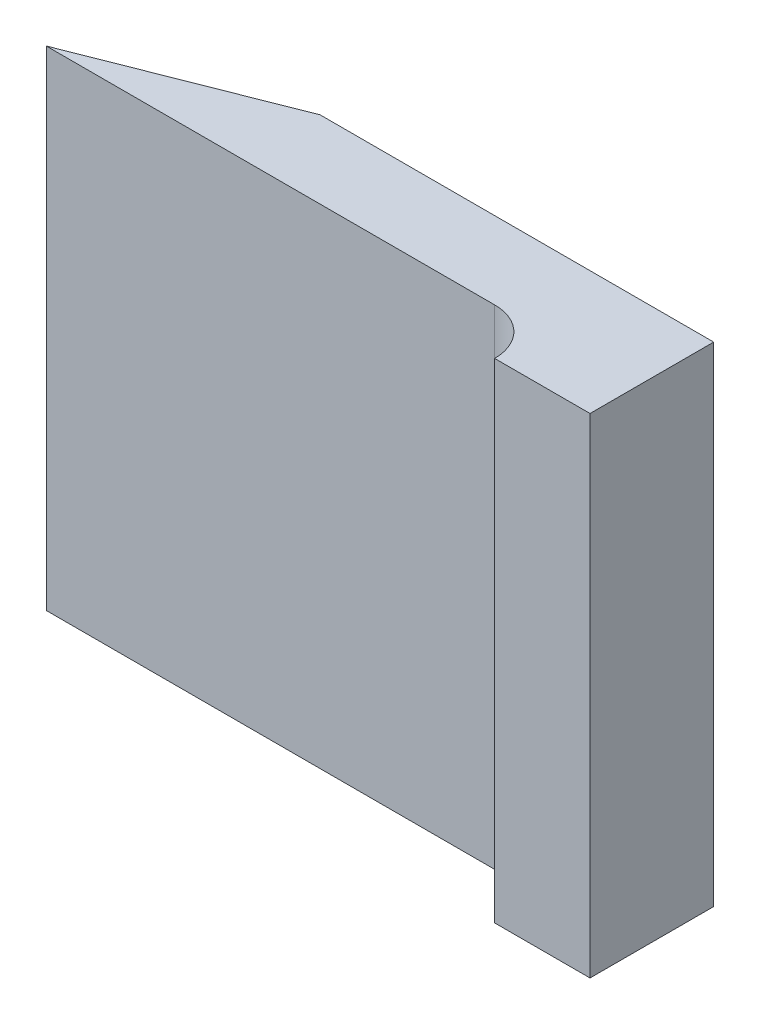
SolidWorks part; units mm, degrees
material "ABS PC"
ref_plane "Front Plane" through (0, 0, 0) normal (0, 0, 1) x (1, 0, 0)
ref_plane "Top Plane" through (0, 0, 0) normal (0, 1, 0) x (1, 0, 0)
ref_plane "Right Plane" through (0, 0, 0) normal (1, 0, 0) x (0, 0, -1)
sketch "Sketch1" plane through (0, 0, 0) normal (0, 0, 1) x (1, 0, 0)
  line L0 (-18.3518, 34.7899) -> (-18.3518, -5.368)
  line L1 (-18.3518, -5.368) -> (30.1209, -5.368)
  line L2 (30.1209, -5.368) -> (30.1209, 34.7899)
  line L3 (30.1209, 34.7899) -> (-18.3518, 34.7899)
extrude "Boss-Extrude1" add sketch "Sketch1" along normal blind 12.7
sketch "Sketch3" plane through (0, 0, 12.7) normal (0, 0, 1) x (1, 0, 0)
  line L0 (-18.3518, -5.368) -> (30.1209, -5.368) construction
  line L1 (-18.3518, 34.7899) -> (22.2882, 34.7899)
  line L2 (-18.3518, 34.7899) -> (-18.3518, -5.368)
  line L3 (-18.3518, -5.368) -> (22.2882, -5.368)
  line L4 (22.2882, 34.7899) -> (22.2882, -5.368)
  dimension "D1" = 40.64
extrude "Cut-Extrude2" cut sketch "Sketch3" against normal blind 6.35
fillet "Fillet7" radius 3.81 1 edges at (22.2882, 14.7109, 6.35)
sketch "Sketch4" plane through (0, 0, 12.7) normal (0, 0, 1) x (1, 0, 0)
  line L1 (22.2882, 34.7899) -> (30.1209, 34.7899)
  line L2 (22.2882, 34.7899) -> (22.2882, -5.368)
  line L3 (22.2882, -5.368) -> (30.1209, -5.368)
  line L4 (30.1209, 34.7899) -> (30.1209, -5.368)
extrude "Cut-Extrude3" cut sketch "Sketch4" against normal blind 2.54
sketch "Sketch5" plane through (0, 34.7899, 0) normal (0, 1, 0) x (1, 0, 0)
  line L0 (-18.3518, 0) -> (-18.3518, -6.35)
  line L1 (-18.3518, -6.35) -> (-2.2102, 0)
  line L2 (30.1209, 0) -> (-18.3518, 0) construction
  line L3 (-2.2102, 0) -> (-18.3518, 0)
extrude "Cut-Extrude4" cut sketch "Sketch5" against normal blind 129.54
